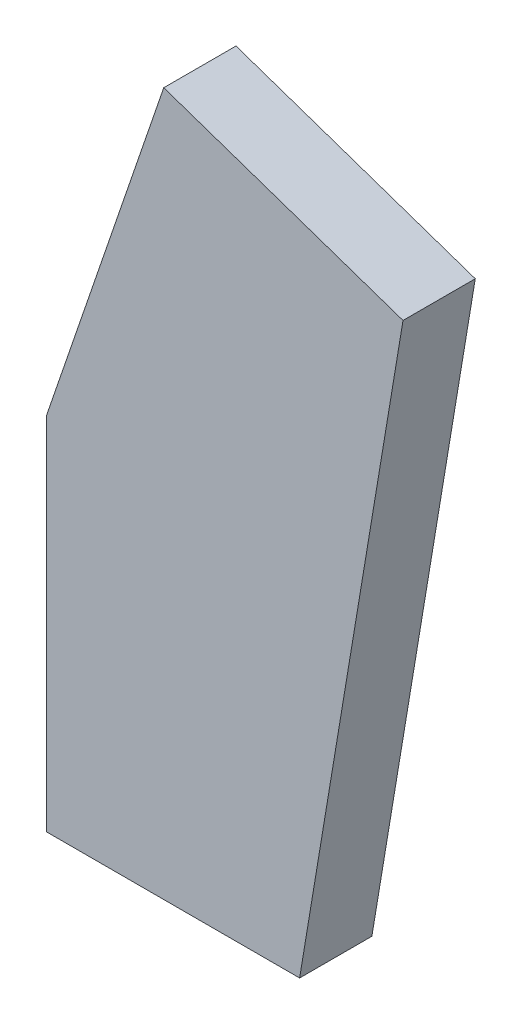
SolidWorks part; units mm, degrees
ref_plane "Front Plane" through (0, 0, 0) normal (0, 0, 1) x (1, 0, 0)
ref_plane "Top Plane" through (0, 0, 0) normal (0, 1, 0) x (1, 0, 0)
ref_plane "Right Plane" through (0, 0, 0) normal (1, 0, 0) x (0, 0, -1)
sketch "Sketch1" plane through (0, 0, 0) normal (0, 0, 1) x (1, 0, 0)
  line L0 (0, -50) -> (0, 0)
  line L1 (0, 0) -> (16.1959, 47.3043)
  line L2 (16.1959, 47.3043) -> (49.3089, 35.9672)
  line L3 (0, -50) -> (35, -50)
  line L4 (49.3089, 35.9672) -> (35, -50)
  dimension "D1" = 50
  dimension "D2" = 35
extrude "Boss-Extrude1" add sketch "Sketch1" along normal blind 10
